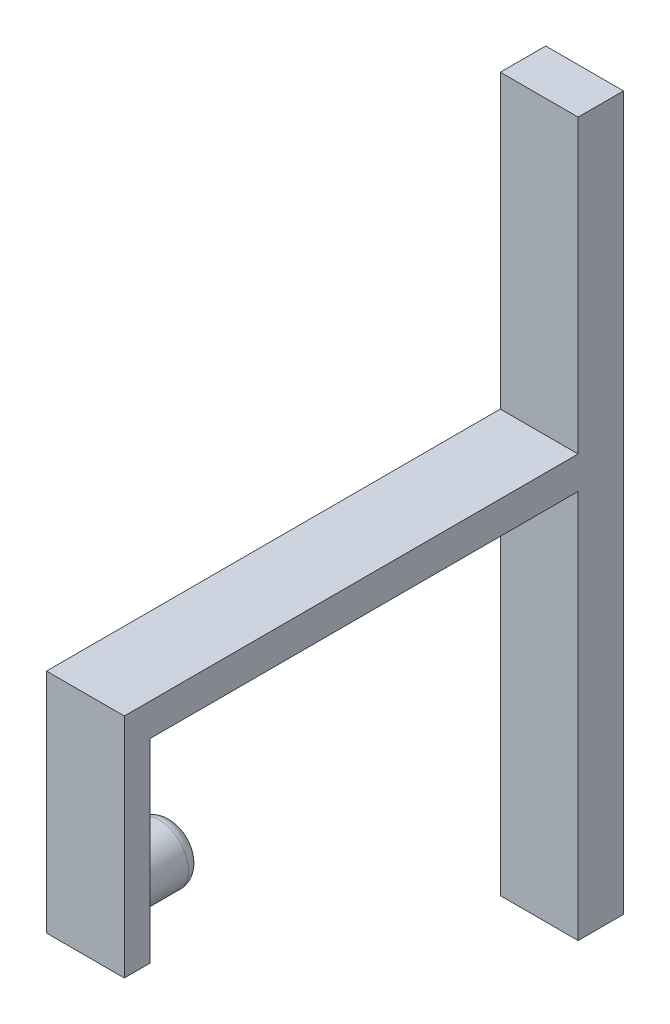
SolidWorks part; units mm, degrees
ref_plane "Plan de face" through (0, 0, 0) normal (0, 0, 1) x (1, 0, 0)
ref_plane "Plan de dessus" through (0, 0, 0) normal (0, 1, 0) x (1, 0, 0)
ref_plane "Plan de droite" through (0, 0, 0) normal (1, 0, 0) x (0, 0, -1)
sketch "Esquisse1" plane through (0, 0, 0) normal (0, 0, 1) x (1, 0, 0)
  line L1 (0, 0) -> (6, 0)
  line L2 (0, 0) -> (0, 55)
  line L3 (0, 55) -> (6, 55)
  line L4 (6, 0) -> (6, 55)
  dimension "D1" = 55
  dimension "D2" = 6
extrude "Boss.-Extru.1" add sketch "Esquisse1" along normal blind 3.5
sketch "Esquisse2" plane through (0, 0, 3.5) normal (0, 0, 1) x (1, 0, 0)
  line L0 (0, 55) -> (0, 30) construction
  line L1 (0, 55) -> (0, 0) construction
  line L2 (6, 0) -> (6, 55) construction
  line L3 (0, 30) -> (6, 30)
  line L4 (0, 30) -> (0, 32.5)
  line L5 (0, 32.5) -> (6, 32.5)
  line L6 (6, 30) -> (6, 32.5)
  dimension "D1" = 25
  dimension "D2" = 2.5
extrude "Boss.-Extru.2" add sketch "Esquisse2" along normal blind 35 contours L4 L5 L6 L3
sketch "Esquisse4" plane through (0, 30, 0) normal (0, -1, 0) x (-1, 0, 0)
  line L0 (0, -38.5) -> (0, -3.5) construction
  line L1 (-6, -38.5) -> (0, -38.5)
  line L2 (-6, -38.5) -> (-6, -36.5)
  line L3 (-6, -36.5) -> (0, -36.5)
  line L4 (0, -38.5) -> (0, -36.5)
  dimension "D1" = 2
extrude "Boss.-Extru.3" add sketch "Esquisse4" along normal blind 15
sketch "Esquisse5" plane through (6, 0, 0) normal (1, 0, 0) x (0, 0, -1)
  line L0 (-3.5, 30) -> (-3.5, 21.4) construction
  line L1 (-3.5, 0) -> (-3.5, 30) construction
  line L2 (-36.5, 30) -> (-36.5, 21.4) construction
  line L3 (-36.5, 15) -> (-36.5, 30) construction
  dimension "D1" = 8.6
  dimension "D2" = 8.6
sketch "Esquisse6" plane through (0, 0, 3.5) normal (0, 0, 1) x (1, 0, 0)
  line L0 (3, 54) -> (3, 51.7) construction
  line L1 (0, 55) -> (6, 55)
  line L2 (0, 55) -> (0, 54)
  line L3 (0, 54) -> (6, 54)
  line L4 (6, 55) -> (6, 54)
  point P6 (0, 0)
  dimension "D1" = 1
  dimension "D2" = 6
  dimension "D3" = 2.3
ref_plane "Plan1" through (0, 0, 0) normal (0, -1, 0) x (-1, 0, 0)
sketch "Esquisse8" plane through (0, 0, 3.5) normal (0, 0, 1) x (1, 0, 0)
  line L0 (6, 21.4) -> (0, 21.4) construction
  line L1 (0, 30) -> (0, 0) construction
  point P5 (3, 21.4)
sketch "Esquisse9" plane through (0, 0, 0) normal (0, 0, -1) x (-1, 0, 0)
  line L0 (0, 21.4) -> (-6, 21.4) construction
  line L1 (0, 55) -> (0, 0) construction
  line L2 (-6, 21.4) -> (0, 21.4) construction
  line L3 (0, 0) -> (-6, 0) construction
  point P8 (-3, 0)
  point P9 (-3, 21.4)
  point P10 (0, 0)
  dimension "D1" = 21.4
sketch "Esquisse10" plane through (0, 0, 36.5) normal (0, 0, -1) x (-1, 0, 0)
  line L0 (-3, 15) -> (-3, 16.7) construction
  line L1 (0, 15) -> (-6, 15) construction
  line L2 (-3, 16.7) -> (-3, 18.95) construction
  circle A0 centre (-3, 18.95) radius 2.25
  dimension "D2" = 4.5
  dimension "D1" = 1.7
extrude "Boss.-Extru.4" add sketch "Esquisse10" along normal blind 4.7
fillet "Congé5" radius 1 1 edges at (0.75, 18.95, 31.8)
